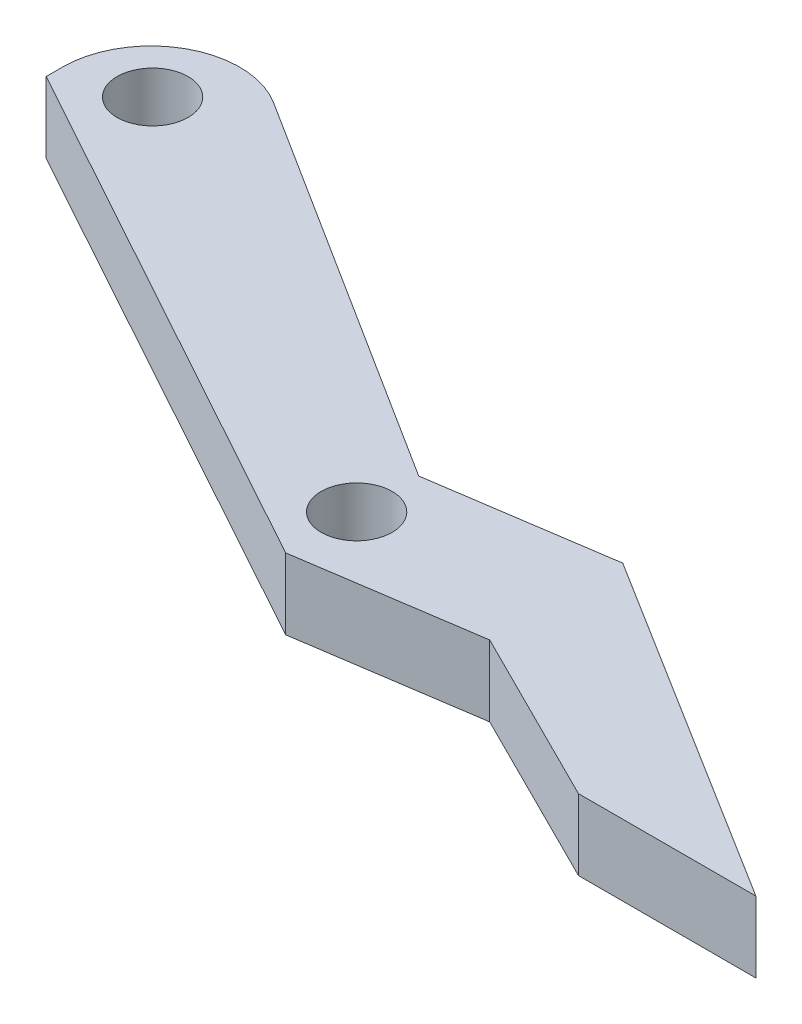
SolidWorks part; units mm, degrees
ref_plane "Front Plane" through (0, 0, 0) normal (0, 0, 1) x (1, 0, 0)
ref_plane "Top Plane" through (0, 0, 0) normal (0, 1, 0) x (1, 0, 0)
ref_plane "Right Plane" through (0, 0, 0) normal (1, 0, 0) x (0, 0, -1)
sketch "Sketch1" plane through (0, 0, 0) normal (0, 1, 0) x (1, 0, 0)
  line L0 (120, 0) -> (100, 0)
  line L1 (0, 0) -> (120, 0) construction
  line L2 (0, 0) -> (0, 60) construction
  line L3 (0, 60) -> (120, 60) construction
  line L4 (120, 0) -> (120, 60) construction
  line L5 (100, 0) -> (80, 10)
  line L6 (80, 10) -> (60, 7)
  line L7 (0, 60) -> (60, 22)
  line L8 (60, 22) -> (80, 25)
  line L9 (80, 25) -> (120, 0)
  line L10 (0, 60) -> (0, 40)
  line L11 (0, 40) -> (60, 7)
  line L12 (60, 7) -> (60, 26.9954) construction
  circle A0 centre (60, 15) radius 4
  circle A1 centre (8, 44) radius 4
  point P5 (120, 0)
  point P6 (100, 0)
  point P7 (79.9553, 0)
  point P8 (80, 10)
  point P9 (80, 25)
  point P10 (79.9553, 0)
  point P11 (80, 10)
  point P12 (80, 25)
  point P15 (0, 60)
  point P18 (60, 22)
  point P19 (0, 40)
  dimension "D11" = 8
  dimension "D1" = 120
  dimension "D2" = 60
  dimension "D3" = 40
  dimension "D4" = 60
  dimension "D5" = 15
  dimension "D6" = 80
  dimension "D7" = 100
  dimension "D8" = 25
  dimension "D9" = 10
  dimension "D10" = 8
  dimension "D12" = 8
  dimension "D13" = 44
  dimension "D14" = 7
extrude "Boss-Extrude1" add sketch "Sketch1" along normal blind 8
fillet "Fillet1" radius 10 1 edges at (0, 4, -60)
